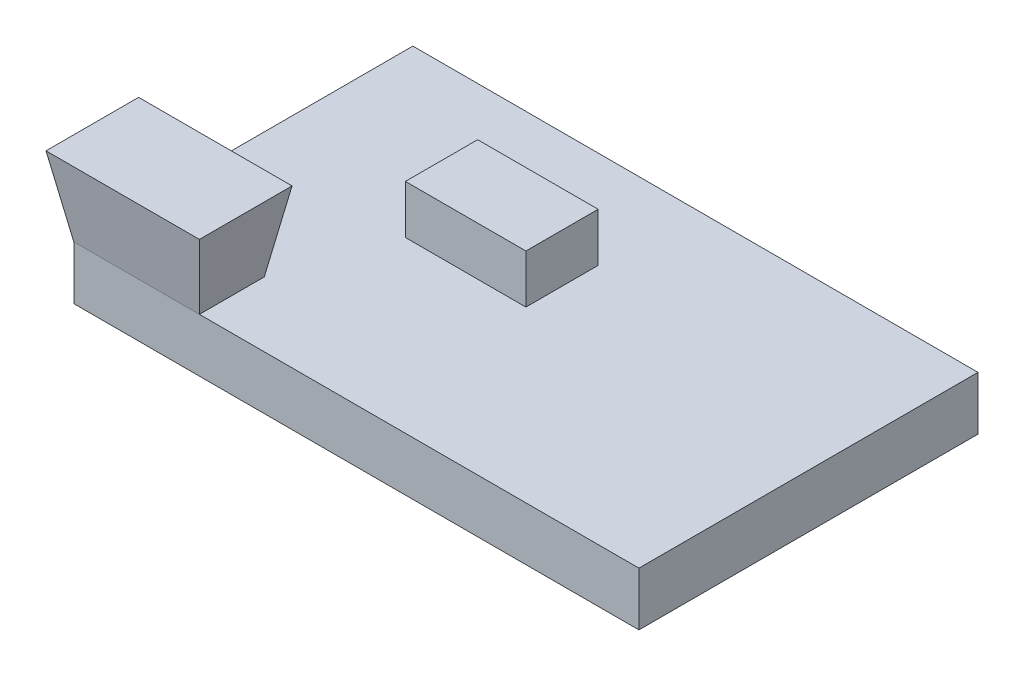
SolidWorks part; units mm, degrees
ref_plane "Front Plane" through (0, 0, 0) normal (0, 0, 1) x (1, 0, 0)
ref_plane "Top Plane" through (0, 0, 0) normal (0, 1, 0) x (1, 0, 0)
ref_plane "Right Plane" through (0, 0, 0) normal (1, 0, 0) x (0, 0, -1)
sketch "Sketch3" plane through (0, 0, 0) normal (0, 1, 0) x (1, 0, 0)
  line L1 (1270, 762) -> (-1270, 762)
  line L2 (1270, 762) -> (1270, -762)
  line L3 (1270, -762) -> (-1270, -762)
  line L4 (-1270, 762) -> (-1270, -762)
  line L5 (1270, 762) -> (-1270, -762) construction
  line L6 (1270, -762) -> (-1270, 762) construction
  point P0 (0, 0)
  dimension "D1" = 2540
  dimension "D2" = 1524
extrude "Boss-Extrude3" add sketch "Sketch3" along normal blind 240.6142
sketch "Sketch4" plane through (0, 240.6142, 0) normal (0, 1, 0) x (1, 0, 0)
  line L5 (-1270, -762) -> (-705.354, -762)
  line L6 (-1270, -762) -> (-1270, -470.6805)
  line L7 (-1270, -470.6805) -> (-705.354, -470.6805)
  line L8 (-705.354, -762) -> (-705.354, -470.6805)
  line M1 (-1270, 762) -> (-1270, -762)
  line M2 (-1270, -762) -> (1270, -762)
extrude "Boss-Extrude4" add sketch "Sketch4" along normal blind 354.33 draft 10 from surface at 0 contours L8 L7 M2 M1 starting at face at (0, 240.6142, 0) draft outward yes
sketch "Sketch6" plane through (0, 240.6142, 0) normal (0, 1, 0) x (1, 0, 0)
  line L1 (-541.6101, 324.6837) -> (541.6101, 324.6837)
  line L2 (-541.6101, 324.6837) -> (-541.6101, -324.6837)
  line L3 (-541.6101, -324.6837) -> (541.6101, -324.6837)
  line L4 (541.6101, 324.6837) -> (541.6101, -324.6837)
  line L5 (-541.6101, 324.6837) -> (541.6101, -324.6837) construction
  line L6 (-541.6101, -324.6837) -> (541.6101, 324.6837) construction
  circle A0 centre (541.6101, 0) radius 324.6837
  point P0 (0, 0)
sketch "Sketch9" plane through (0, 240.6142, 0) normal (0, 1, 0) x (1, 0, 0)
  line L1 (0, 0) -> (-541.6101, 0)
  line L2 (0, 0) -> (0, 324.6837)
  line L3 (0, 324.6837) -> (-541.6101, 324.6837)
  line L4 (-541.6101, 0) -> (-541.6101, 324.6837)
  point P6 (0, 0)
  point P7 (0, 0)
  point P8 (0, 0)
extrude "Boss-Extrude5" add sketch "Sketch9" along normal blind 218.44
